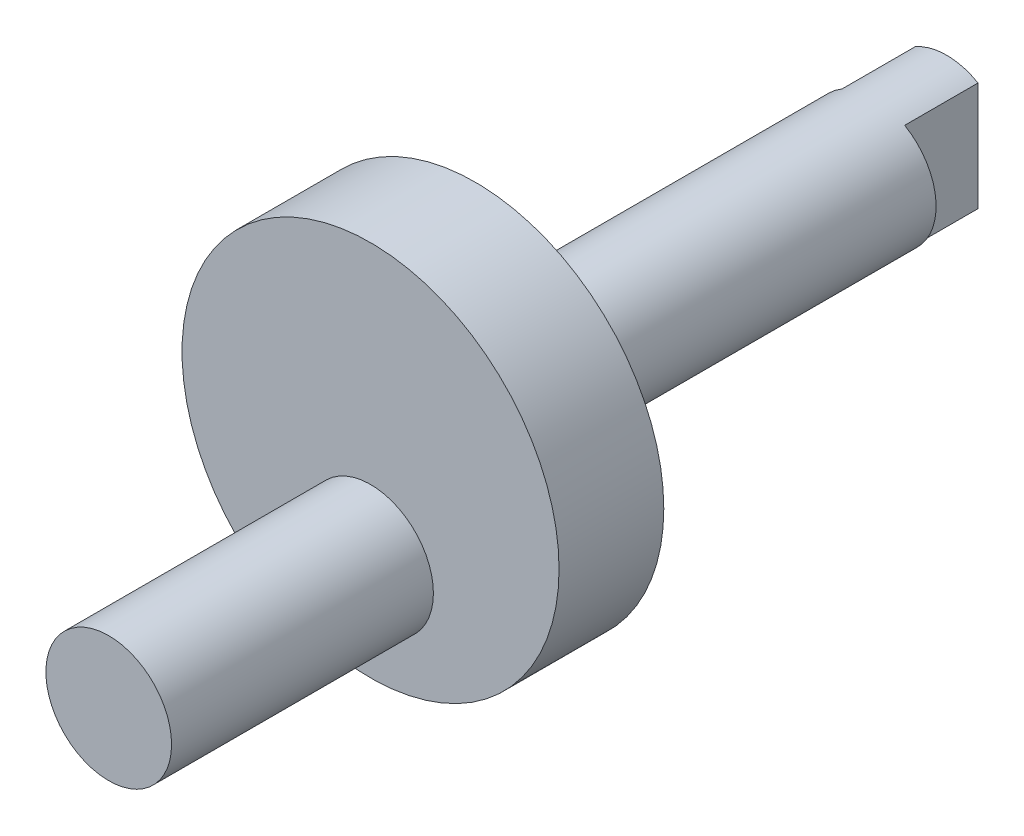
SolidWorks part; units mm, degrees
material "CP-Ti comercialmente puro UNS R50400 (SS)"
ref_plane "Plano frontal" through (0, 0, 0) normal (0, 0, 1) x (1, 0, 0)
ref_plane "Plano superior" through (0, 0, 0) normal (0, 1, 0) x (1, 0, 0)
ref_plane "Plano direito" through (0, 0, 0) normal (1, 0, 0) x (0, 0, -1)
sketch "Esboço1" plane through (0, 0, 0) normal (0, 0, 1) x (1, 0, 0)
  circle A0 centre (0, 0) radius 6
  dimension "D1" = 12
extrude "Ressalto-extrusão1" add sketch "Esboço1" along normal blind 45
sketch "Esboço2" plane through (0, 0, 45) normal (0, 0, 1) x (1, 0, 0)
  circle A0 centre (0, 0) radius 18
  dimension "D1" = 36
extrude "Ressalto-extrusão2" add sketch "Esboço2" along normal blind 10
sketch "Esboço3" plane through (0, 0, 55) normal (0, 0, 1) x (1, 0, 0)
  circle A0 centre (0, -8) radius 6
  dimension "D1" = 12
  dimension "D2" = 0
  dimension "D3" = 8
extrude "Ressalto-extrusão3" add sketch "Esboço3" along normal blind 25
sketch "Esboço4" plane through (0, 0, 0) normal (0, 0, -1) x (-1, 0, 0)
  line L1 (-7.5296, 5.3006) -> (-3, 5.3006)
  line L2 (-7.5296, 5.3006) -> (-7.5296, -6.168)
  line L3 (-7.5296, -6.168) -> (-3, -6.168)
  line L4 (-3, 5.3006) -> (-3, -6.168)
  line L5 (9.0593, 7.1318) -> (3, 7.1318)
  line L6 (9.0593, 7.1318) -> (9.0593, -8.481)
  line L7 (9.0593, -8.481) -> (3, -8.481)
  line L8 (3, 7.1318) -> (3, -8.481)
  dimension "D1" = 3
  dimension "D2" = 3
extrude "Corte-extrusão1" cut sketch "Esboço4" against normal blind 7
